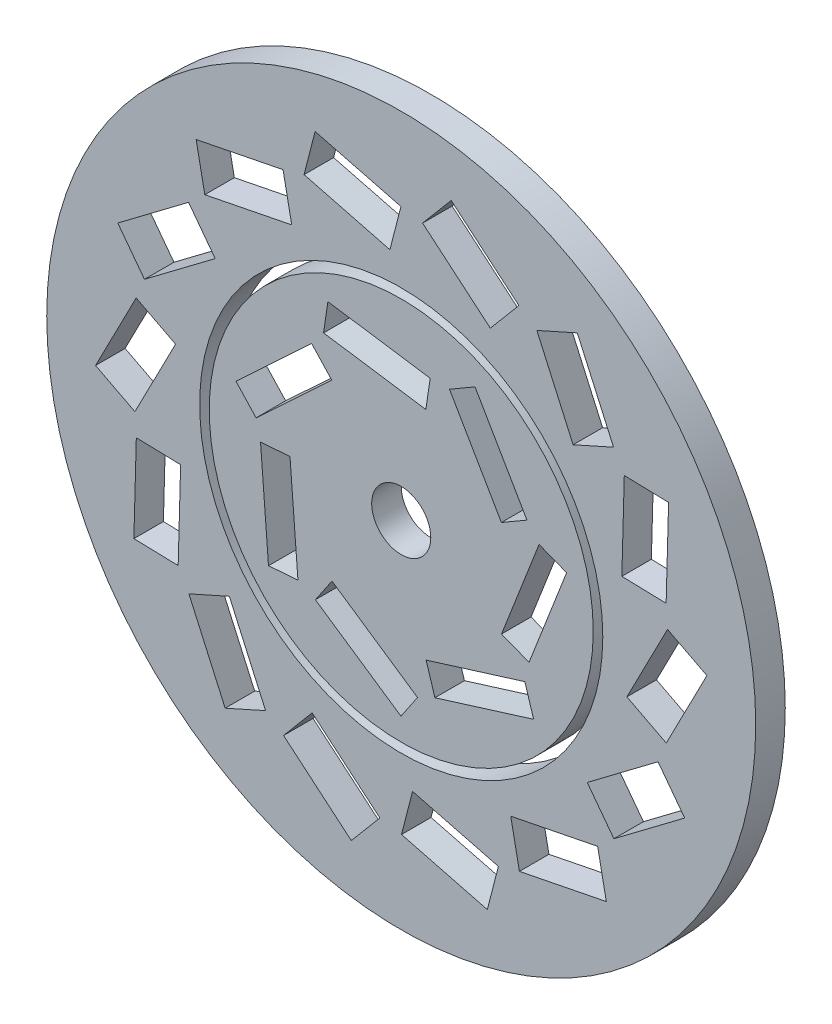
SolidWorks part; units mm, degrees
ref_plane "Front Plane" through (0, 0, 0) normal (0, 0, 1) x (1, 0, 0)
ref_plane "Top Plane" through (0, 0, 0) normal (0, 1, 0) x (1, 0, 0)
ref_plane "Right Plane" through (0, 0, 0) normal (1, 0, 0) x (0, 0, -1)
sketch "Sketch1" plane through (0, 0, 0) normal (0, 0, 1) x (1, 0, 0)
  line L0 (0, 0) -> (29.446, 34.0285) construction
  line L1 (24.9863, 51.6739) -> (42.5546, 21.4026)
  line L2 (24.9863, 51.6739) -> (16.3373, 46.6544)
  line L3 (42.5546, 21.4026) -> (33.9056, 16.383)
  line L4 (16.3373, 46.6544) -> (33.9056, 16.383)
  line L5 (24.9863, 51.6739) -> (33.9056, 16.383) construction
  line L6 (42.5546, 21.4026) -> (16.3373, 46.6544) construction
  line L39 (0, 0) -> (58.8919, 68.0569) construction
  line L40 (58.1792, 51.3016) -> (45.9153, 78.6803)
  line L41 (58.1792, 51.3016) -> (71.8685, 57.4335)
  line L42 (45.9153, 78.6803) -> (59.6046, 84.8123)
  line L43 (71.8685, 57.4335) -> (59.6046, 84.8123)
  line L44 (58.1792, 51.3016) -> (59.6046, 84.8123) construction
  line L45 (45.9153, 78.6803) -> (71.8685, 57.4335) construction
  line L46 (75.5063, 50.9666) -> (90.5006, 50.5517)
  line L47 (89.6708, 20.5632) -> (90.5006, 50.5517)
  line L48 (74.6765, 20.9781) -> (89.6708, 20.5632)
  line L49 (74.6765, 20.9781) -> (75.5063, 50.9666)
  line L50 (90.1424, 13.1584) -> (103.4718, 6.2788)
  line L51 (89.7126, -20.3799) -> (103.4718, 6.2788)
  line L52 (76.3833, -13.5003) -> (89.7126, -20.3799)
  line L53 (76.3833, -13.5003) -> (90.1424, 13.1584)
  line L54 (86.9247, -27.256) -> (95.9491, -39.2377)
  line L55 (71.9858, -57.2865) -> (95.9491, -39.2377)
  line L56 (62.9614, -45.3048) -> (71.9858, -57.2865)
  line L57 (62.9614, -45.3048) -> (86.9247, -27.256)
  line L58 (66.4905, -62.2721) -> (69.4226, -76.9827)
  line L59 (40.0013, -82.8468) -> (69.4226, -76.9827)
  line L60 (37.0692, -68.1362) -> (40.0013, -82.8468)
  line L61 (37.0692, -68.1362) -> (66.4905, -62.2721)
  line L62 (32.8871, -84.9544) -> (29.146, -99.4804)
  line L63 (0.094, -91.9983) -> (29.146, -99.4804)
  line L64 (3.8351, -77.4723) -> (0.094, -91.9983)
  line L65 (3.8351, -77.4723) -> (32.8871, -84.9544)
  line L66 (-7.2301, -90.8104) -> (-16.9033, -102.2747)
  line L67 (-39.8319, -82.9284) -> (-16.9033, -102.2747)
  line L68 (-30.1587, -71.4641) -> (-39.8319, -82.9284)
  line L69 (-30.1587, -71.4641) -> (-7.2301, -90.8104)
  line L70 (-45.9153, -78.6803) -> (-59.6046, -84.8123)
  line L71 (-71.8685, -57.4335) -> (-59.6046, -84.8123)
  line L72 (-58.1792, -51.3016) -> (-71.8685, -57.4335)
  line L73 (-58.1792, -51.3016) -> (-45.9153, -78.6803)
  line L74 (-75.5063, -50.9666) -> (-90.5006, -50.5517)
  line L75 (-89.6708, -20.5632) -> (-90.5006, -50.5517)
  line L76 (-74.6765, -20.9781) -> (-89.6708, -20.5632)
  line L77 (-74.6765, -20.9781) -> (-75.5063, -50.9666)
  line L78 (-90.1424, -13.1584) -> (-103.4718, -6.2788)
  line L79 (-89.7126, 20.3799) -> (-103.4718, -6.2788)
  line L80 (-76.3833, 13.5003) -> (-89.7126, 20.3799)
  line L81 (-76.3833, 13.5003) -> (-90.1424, -13.1584)
  line L82 (-86.9247, 27.256) -> (-95.9491, 39.2377)
  line L83 (-71.9858, 57.2865) -> (-95.9491, 39.2377)
  line L84 (-62.9614, 45.3048) -> (-71.9858, 57.2865)
  line L85 (-62.9614, 45.3048) -> (-86.9247, 27.256)
  line L86 (-66.4905, 62.2721) -> (-69.4226, 76.9827)
  line L87 (-40.0013, 82.8468) -> (-69.4226, 76.9827)
  line L88 (-37.0692, 68.1362) -> (-40.0013, 82.8468)
  line L89 (-37.0692, 68.1362) -> (-66.4905, 62.2721)
  line L90 (-32.8871, 84.9544) -> (-29.146, 99.4804)
  line L91 (-0.094, 91.9983) -> (-29.146, 99.4804)
  line L92 (-3.8351, 77.4723) -> (-0.094, 91.9983)
  line L93 (-3.8351, 77.4723) -> (-32.8871, 84.9544)
  line L94 (7.2301, 90.8104) -> (16.9033, 102.2747)
  line L95 (39.8319, 82.9284) -> (16.9033, 102.2747)
  line L96 (30.1587, 71.4641) -> (39.8319, 82.9284)
  line L97 (30.1587, 71.4641) -> (7.2301, 90.8104)
  line L98 (46.662, 16.3155) -> (33.9486, -16.2939)
  line L99 (55.9789, 12.6831) -> (43.2656, -19.9262)
  line L100 (43.2656, -19.9262) -> (33.9486, -16.2939)
  line L101 (55.9789, 12.6831) -> (46.662, 16.3155)
  line L102 (41.8492, -26.3093) -> (8.4276, -36.7011)
  line L103 (44.8183, -35.8583) -> (11.3967, -46.2502)
  line L104 (11.3967, -46.2502) -> (8.4276, -36.7011)
  line L105 (44.8183, -35.8583) -> (41.8492, -26.3093)
  line L106 (5.5232, -49.1226) -> (-23.4396, -29.4717)
  line L107 (-0.0914, -57.3977) -> (-29.0541, -37.7468)
  line L108 (-29.0541, -37.7468) -> (-23.4396, -29.4717)
  line L109 (-0.0914, -57.3977) -> (5.5232, -49.1226)
  line L110 (-34.962, -34.9456) -> (-37.6563, -0.0495)
  line L111 (-44.9323, -35.7154) -> (-47.6266, -0.8193)
  line L112 (-47.6266, -0.8193) -> (-37.6563, -0.0495)
  line L113 (-44.9323, -35.7154) -> (-34.962, -34.9456)
  line L114 (-49.12, 5.5461) -> (-23.517, 29.41)
  line L115 (-55.9383, 12.8613) -> (-30.3352, 36.7251)
  line L116 (-30.3352, 36.7251) -> (-23.517, 29.41)
  line L117 (-55.9383, 12.8613) -> (-49.12, 5.5461)
  line L118 (-26.2897, 41.8615) -> (8.3311, 36.7232)
  line L119 (-24.8216, 51.7532) -> (9.7992, 46.6148)
  line L120 (9.7992, 46.6148) -> (8.3311, 36.7232)
  line L121 (-24.8216, 51.7532) -> (-26.2897, 41.8615)
  circle A0 centre (0, 0) radius 120
  circle A1 centre (0, 0) radius 65
  circle A2 centre (0, 0) radius 10
  circle A3 centre (0, 0) radius 65
  circle A4 centre (0, 0) radius 65
  circle A5 centre (0, 0) radius 65
  circle A6 centre (0, 0) radius 65
  circle A7 centre (0, 0) radius 65
  circle A8 centre (0, 0) radius 65
  circle A9 centre (0, 0) radius 68.2339
  point P44 (0, 0)
  point P45 (0, 0)
  point P102 (0, 0)
  point P103 (0, 0)
  dimension "D1" = 240
  dimension "D2" = 130
  dimension "D3" = 20
  dimension "D4" = 45
  dimension "D5" = 10
  dimension "D6" = 109
  dimension "D7" = 35
  dimension "D9" = 90
  dimension "D10" = 15
  dimension "D11" = 30
  dimension "D12" = 115
  dimension "D13" = 14
  dimension "D8" = 7
extrude "Boss-Extrude1" add sketch "Sketch1" along normal blind 10
